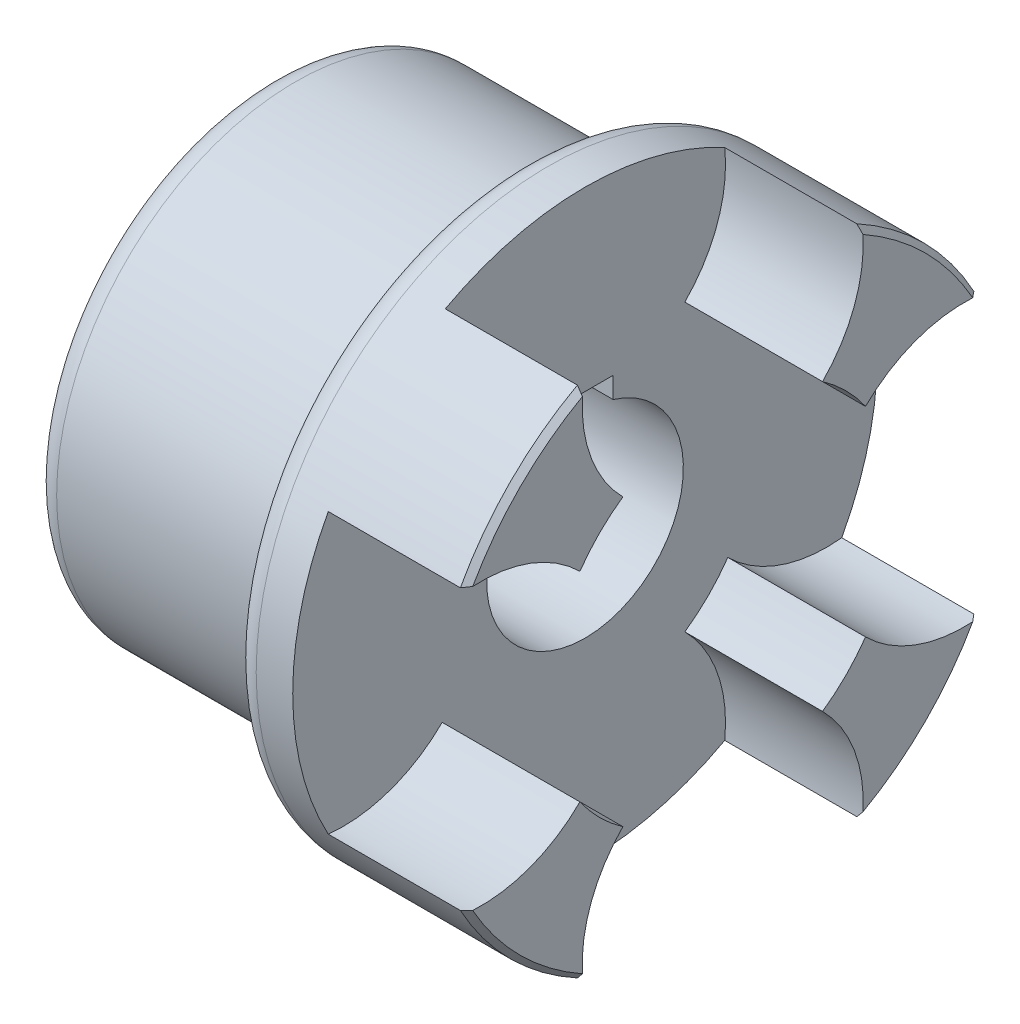
SolidWorks part; units mm, degrees
material "1.0037 (S235JR)"
ref_plane "Спереди" through (0, 0, 0) normal (0, 0, 1) x (1, 0, 0)
ref_plane "Сверху" through (0, 0, 0) normal (0, 1, 0) x (1, 0, 0)
ref_plane "Справа" through (0, 0, 0) normal (1, 0, 0) x (0, 0, -1)
sketch "Эскиз1" plane through (0, 0, 0) normal (0, 0, 1) x (1, 0, 0)
  line L0 (-70.2451, -25.1422) -> (10.2549, -25.1422) construction
  line L1 (-70.2451, -6.6422) -> (-70.2451, 12.8578)
  line L2 (-70.2451, -6.6422) -> (-69.2451, -7.6422)
  line L3 (-65.7451, 17.3578) -> (-29.7451, 17.3578)
  line L4 (-25.2451, 21.8578) -> (-25.2451, 22.3578)
  line L5 (10.2549, -6.6422) -> (10.2549, 25.8578)
  line L6 (-69.2451, -7.6422) -> (9.2549, -7.6422)
  line L7 (-20.7451, 26.8578) -> (9.2549, 26.8578)
  line L8 (9.2549, -7.6422) -> (10.2549, -6.6422)
  line L9 (10.2549, 25.8578) -> (9.2549, 26.8578)
  arc A0 (-20.7451, 26.8578) -> (-25.2451, 22.3578) centre (-20.7451, 22.3578) ccw
  arc A1 (-25.2451, 21.8578) -> (-29.7451, 17.3578) centre (-29.7451, 21.8578) cw
  arc A2 (-65.7451, 17.3578) -> (-70.2451, 12.8578) centre (-65.7451, 12.8578) ccw
  point P4 (-70.2451, -7.6422)
  point P8 (10.2549, 26.8578)
  point P9 (10.2549, -7.6422)
  dimension "D1" = 4.5
  dimension "D2" = 4.5
revolve "Повернуть1" add sketch "Эскиз1" angle 360 about L0
sketch "Эскиз3" plane through (10.2549, 0, 0) normal (1, 0, 0) x (0, 0, -1)
  circle A33 centre (0, -25.1422) radius 43 construction
  arc A35 (-17.7619, -50.5492) -> (17.7619, -50.5492) centre (0, -68.1422) ccw
  arc A36 (-25.407, -7.3803) -> (-25.407, -42.9041) centre (-43, -25.1422) ccw
  arc A37 (17.7619, 0.2648) -> (-17.7619, 0.2648) centre (0, 17.8578) ccw
  arc A38 (25.407, -42.9041) -> (25.407, -7.3803) centre (43, -25.1422) ccw
  arc A39 (17.7619, -50.5492) -> (25.407, -42.9041) centre (0, -25.1422) ccw
  arc A40 (-25.407, -42.9041) -> (-17.7619, -50.5492) centre (0, -25.1422) ccw
  arc A41 (-17.7619, 0.2648) -> (-25.407, -7.3803) centre (0, -25.1422) ccw
  arc A42 (25.407, -7.3803) -> (17.7619, 0.2648) centre (0, -25.1422) ccw
extrude "Вырез-Вытянуть1" cut sketch "Эскиз3" against normal blind 24.5
sketch "Эскиз4" plane through (-14.2451, 0, 0) normal (1, 0, 0) x (0, 0, -1)
  line L0 (-5, -11.6965) -> (5, -11.6965)
  line L1 (5, -11.6965) -> (5, -4.6422)
  line L2 (-5, -11.6965) -> (-5, -4.6422)
  line L3 (-5, -4.6422) -> (5, -4.6422)
extrude "Вырез-Вытянуть2" cut sketch "Эскиз4" against normal through all
